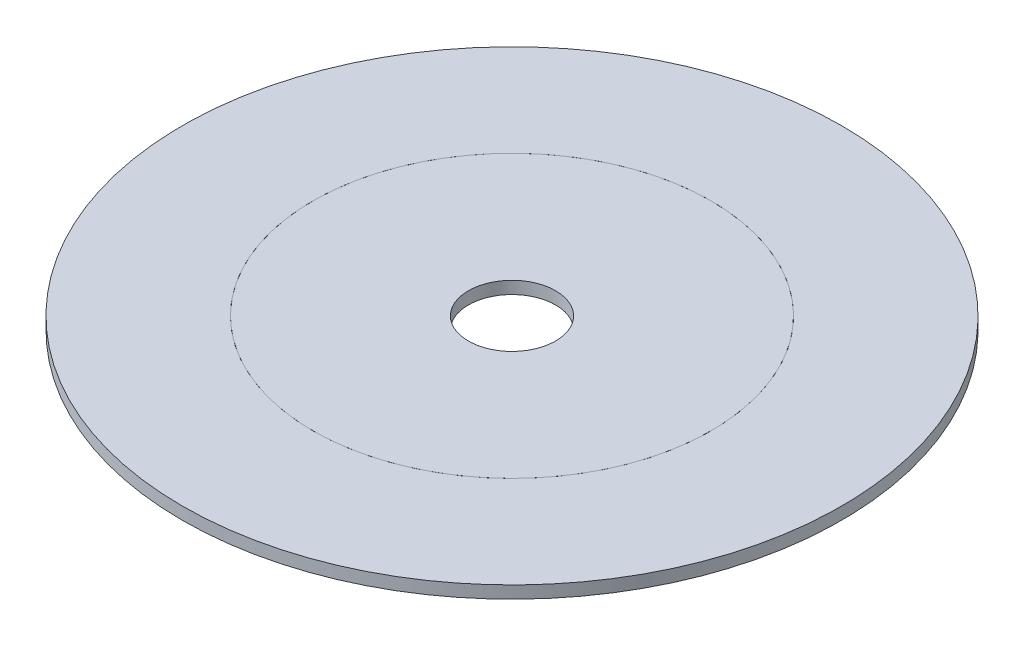
SolidWorks part; units mm, degrees
ref_plane "Front Plane" through (0, 0, 0) normal (0, 0, 1) x (1, 0, 0)
ref_plane "Top Plane" through (0, 0, 0) normal (0, 1, 0) x (1, 0, 0)
ref_plane "Right Plane" through (0, 0, 0) normal (1, 0, 0) x (0, 0, -1)
sketch "Sketch1" plane through (0, 0, 0) normal (0, 1, 0) x (1, 0, 0)
  circle A0 centre (0, 0) radius 14.5
  circle A1 centre (0, 0) radius 24
  dimension "D1" = 48
  dimension "D2" = 29
extrude "Boss-Extrude1" add sketch "Sketch1" along normal blind 0.9
sketch "Sketch2" plane through (0, 0, 0) normal (0, -1, 0) x (1, 0, 0)
  circle A0 centre (0, 0) radius 14.5 construction
  circle A1 centre (0, 0) radius 14.5
  circle A2 centre (0, 0) radius 3.175
  dimension "D1" = 6.35
extrude "Boss-Extrude2" add sketch "Sketch2" against normal blind 0.9 separate body
